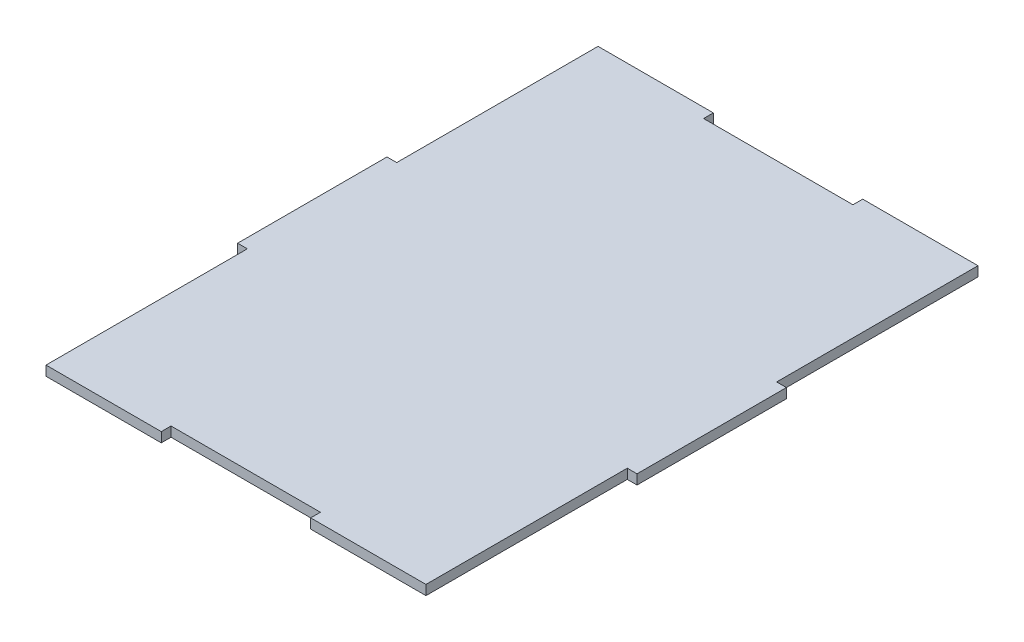
SolidWorks part; units mm, degrees
ref_plane "Alzado" through (0, 0, 0) normal (0, 0, 1) x (1, 0, 0)
ref_plane "Planta" through (0, 0, 0) normal (0, 1, 0) x (1, 0, 0)
ref_plane "Vista lateral" through (0, 0, 0) normal (1, 0, 0) x (0, 0, -1)
sketch "Croquis1" plane through (0, 0, 0) normal (0, 1, 0) x (1, 0, 0)
  line L0 (84.5, 170) -> (120, 170)
  line L1 (3, 170) -> (38.5, 170)
  line L2 (3, 170) -> (3, 108)
  line L3 (3, 0) -> (38.5, 0)
  line L4 (120, 170) -> (120, 108)
  line L5 (3, 108) -> (0, 108)
  line L7 (3, 62) -> (0, 62)
  line L8 (0, 108) -> (0, 62)
  line L9 (120, 108) -> (123, 108)
  line L11 (120, 62) -> (123, 62)
  line L12 (123, 108) -> (123, 62)
  line L14 (84.5, 0) -> (84.5, 3)
  line L15 (84.5, 3) -> (38.5, 3)
  line L16 (38.5, 0) -> (38.5, 3)
  line L18 (38.5, 170) -> (38.5, 167)
  line L19 (38.5, 167) -> (84.5, 167)
  line L20 (84.5, 170) -> (84.5, 167)
  line L21 (120, 62) -> (120, 0)
  line L22 (84.5, 0) -> (120, 0)
  line L23 (3, 62) -> (3, 0)
  line L24 (84.5, 170) -> (38.5, 170) construction
  line L25 (84.5, 0) -> (38.5, 0) construction
  line L26 (61.5, 0) -> (61.5, 170) construction
  line L27 (3, 62) -> (3, 108) construction
  line L28 (120, 62) -> (120, 108) construction
  line L29 (120, 85) -> (3, 85) construction
  line L30 (3, 0) -> (0, 0) construction
  line L31 (0, 0) -> (0, 62) construction
  point P22 (0, 85)
  point P23 (61.5, 85)
  point P24 (123, 85)
  point P27 (61.5, 85)
  point P28 (0, 0)
  dimension "D1" = 3
  dimension "D2" = 3
  dimension "D3" = 3
  dimension "D4" = 3
  dimension "D5" = 46
  dimension "D6" = 46
  dimension "D7" = 170
  dimension "D8" = 123
extrude "Saliente-Extruir1" add sketch "Croquis1" along normal blind 3
